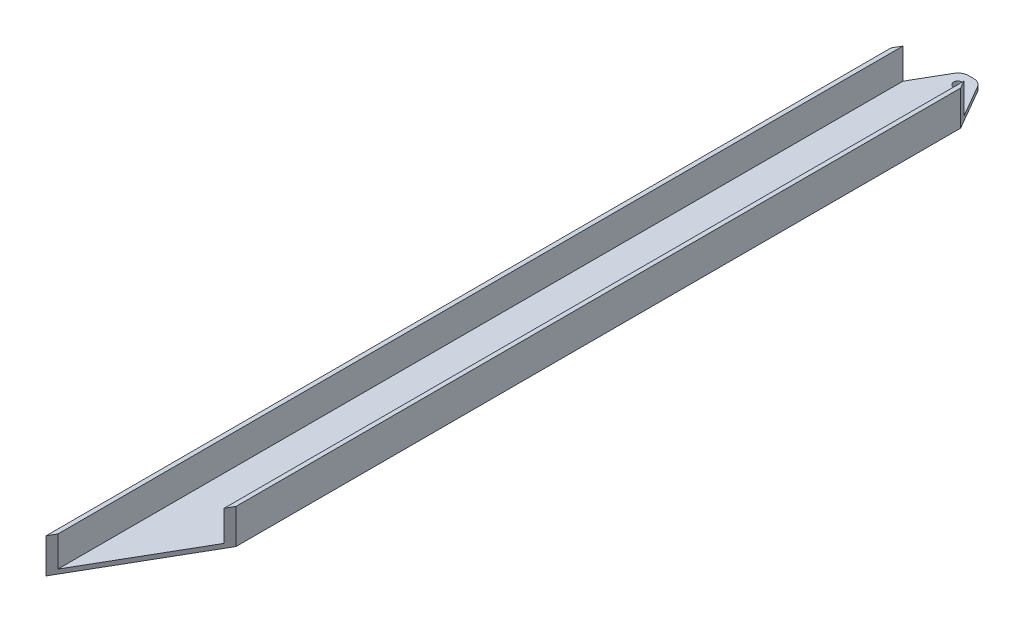
SolidWorks part; units mm, degrees
ref_plane "Front Plane" through (0, 0, 0) normal (0, 0, 1) x (1, 0, 0)
ref_plane "Top Plane" through (0, 0, 0) normal (0, 1, 0) x (1, 0, 0)
ref_plane "Right Plane" through (0, 0, 0) normal (1, 0, 0) x (0, 0, -1)
sketch "Sketch1" plane through (0, 0, 0) normal (0, 0, 1) x (1, 0, 0)
  line L0 (-22.225, -9.525) -> (-22.225, 12.7)
  line L1 (-25.4, -12.7) -> (25.4, -12.7)
  line L2 (-25.4, -12.7) -> (-25.4, 12.7)
  line L3 (-22.225, -9.525) -> (22.225, -9.525)
  line L4 (25.4, -12.7) -> (25.4, 12.7)
  line L5 (22.225, -9.525) -> (22.225, 12.7)
  line L6 (-25.4, 12.7) -> (-22.225, 12.7)
  line L7 (25.4, 12.7) -> (22.225, 12.7)
  dimension "D1" = 25.4
  dimension "D2" = 50.8
  dimension "D3" = 3.175
extrude "Boss-Extrude1" add sketch "Sketch1" along normal blind 650.24
sketch "Sketch2" plane through (0, -12.7, 0) normal (0, -1, 0) x (1, 0, 0)
  line L0 (-25.4, 650.24) -> (25.4, 562.2518)
  line L2 (25.4, 650.24) -> (25.4, 0) construction
  line L3 (25.4, 562.2518) -> (25.4, 650.24)
  line L5 (25.4, 650.24) -> (-25.4, 650.24)
  line L6 (-25.4, 650.24) -> (-25.4, 0) construction
  dimension "D1" = 30
extrude "Cut-Extrude1" cut sketch "Sketch2" against normal through all
sketch "Sketch3" plane through (0, 12.7, 0) normal (0, 1, 0) x (1, 0, 0)
  line L0 (22.225, 0) -> (-22.225, 0) construction
  line L1 (22.225, 0) -> (-22.225, 0) construction
  line L2 (0, 0) -> (0, -6.35) construction
  line L3 (-6.35, 0) -> (6.35, 0)
  line L4 (6.35, 0) -> (25.4, -32.9956)
  line L5 (25.4, -562.2518) -> (25.4, 0) construction
  line L6 (25.4, -32.9956) -> (25.4, 20.9363)
  line L7 (-6.35, 0) -> (-25.4, -32.9956)
  line L9 (-25.4, -650.24) -> (-25.4, 0) construction
  line L10 (-25.4, -32.9956) -> (-25.4, 20.9363)
  line L11 (-25.4, 20.9363) -> (25.4, 20.9363)
  circle A0 centre (0, -9.525) radius 3.175
  point P9 (0, 0)
  dimension "D2" = 6.35
  dimension "D1" = 6.35
  dimension "D3" = 6.35
  dimension "D4" = 60
extrude "Cut-Extrude2" cut sketch "Sketch3" against normal through all
fillet "Fillet1" radius 7.62 2 edges at (-6.35, -11.1125, 0) (6.35, -11.1125, 0)
